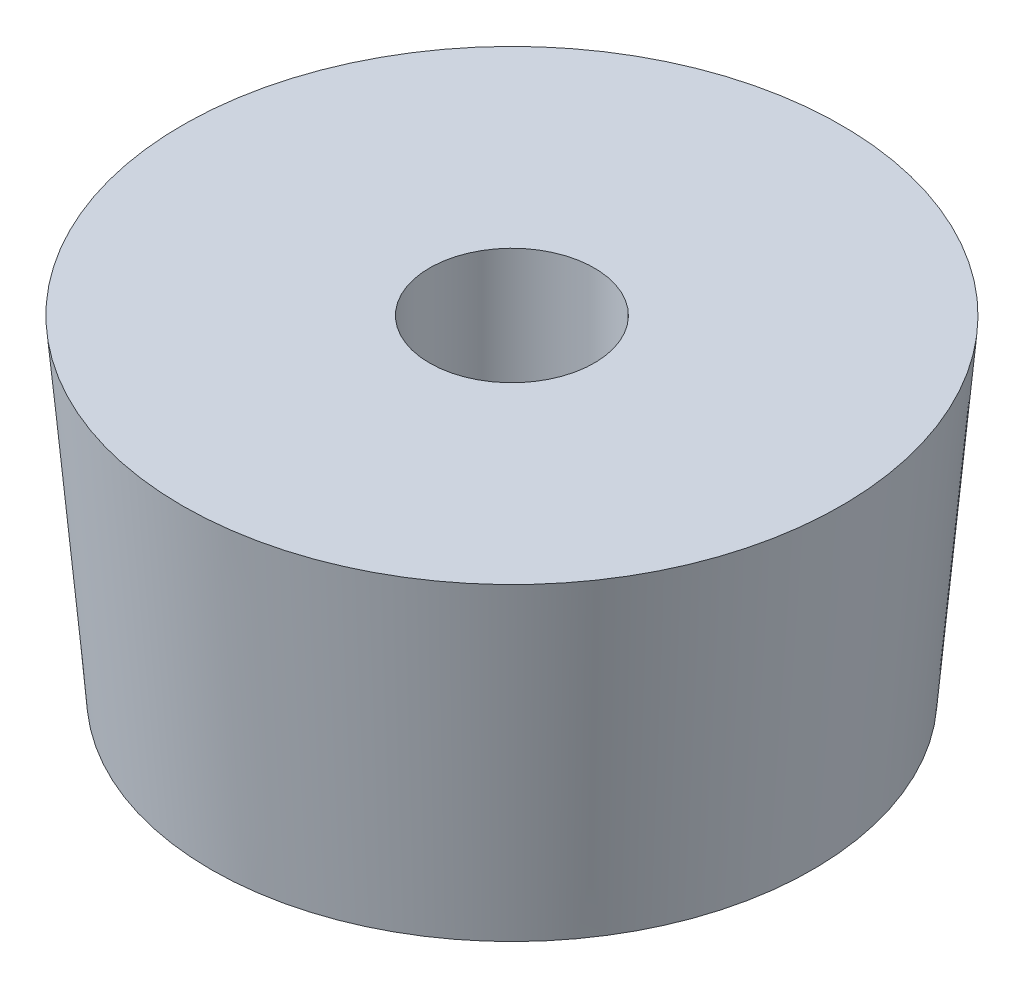
SolidWorks part; units mm, degrees
ref_plane "Front Plane" through (0, 0, 0) normal (0, 0, 1) x (1, 0, 0)
ref_plane "Top Plane" through (0, 0, 0) normal (0, 1, 0) x (1, 0, 0)
ref_plane "Right Plane" through (0, 0, 0) normal (1, 0, 0) x (0, 0, -1)
sketch "Sketch1" plane through (0, 0, 0) normal (0, 1, 0) x (1, 0, 0)
  circle A0 centre (0, 0) radius 12.7
  dimension "D1" = 25.4
extrude "Boss-Extrude1" add sketch "Sketch1" against normal blind 12.7 draft 5
sketch "Sketch2" plane through (0, 0, 0) normal (0, 1, 0) x (1, 0, 0)
  circle A0 centre (0, 0) radius 3.175
  dimension "D1" = 6.35
extrude "Cut-Extrude1" cut sketch "Sketch2" against normal through all
sketch "Sketch3" plane through (0, 0, 0) normal (0, 0, 1) x (1, 0, 0)
  line L0 (0, -13.4041) -> (0, 0) construction
sketch "Sketch7" plane through (0, -12.7, 0) normal (0, -1, 0) x (1, 0, 0)
  line L0 (0, 0) -> (-8.636, 0) construction
  line L1 (0, 0) -> (4.318, 7.479) construction
  circle A0 centre (-8.636, 0) radius 1.27
  circle A2 centre (4.318, 7.479) radius 1.27
  dimension "D1" = 2.54
  dimension "D2" = 8.636
  dimension "D4" = 120
  dimension "D3" = 2
extrude "Cut-Extrude2" cut sketch "Sketch7" against normal blind 7.62 contours A2 | A0
equation "\"D1@Sketch7\" = \"D1@Sketch1\" / 10"
equation "\"D2@Sketch7\" = ( \"D1@Sketch1\" / 2 ) - ( \"D1@Sketch7\" * 1.6 )"
